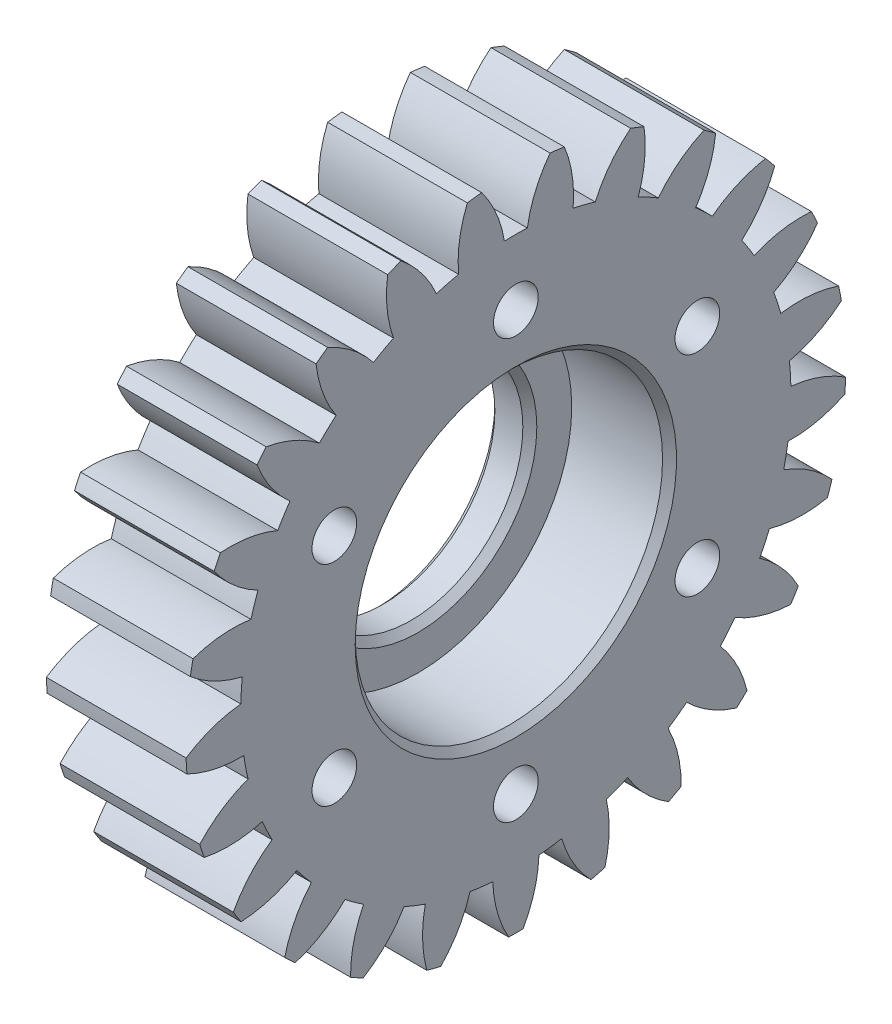
SolidWorks part; units mm, degrees
ref_plane "Plane1" through (0, 0, 0) normal (0, 0, 1) x (1, 0, 0)
ref_plane "Plane2" through (0, 0, 0) normal (0, 1, 0) x (1, 0, 0)
ref_plane "Plane3" through (0, 0, 0) normal (1, 0, 0) x (0, 0, -1)
sketch "HoldingSke" plane through (0, 0, 0) normal (0, 1, 0) x (1, 0, 0)
  line L0 (0, 0) -> (0.5179, -0.2415)
  line L1 (-15, 0) -> (100, 0) construction
  line L2 (0, 0) -> (-2.1039, 2.3779)
  line L3 (0, 0) -> (-11.863, 4.5341)
  line L4 (0, 0) -> (7.8269, 3.6497)
  line L5 (0, 0) -> (-46.8476, -17.4728)
  line L6 (0, 0) -> (-8.2896, -5.593)
  line L7 (-2.1039, 2.3779) -> (8.6586, 51.2059)
  line L8 (-76.2, 54.61) -> (-74.8, 54.61)
  line L9 (-71.009, 38.7566) -> (-53.1078, 45.2721)
  line L10 (-76.2, 71.12) -> (104.1128, 71.12)
  line L11 (0, 0) -> (-10, 0)
  line L12 (-76.2, 101.6) -> (-76.147, 101.6)
  line L13 (24.9733, 27.94) -> (52.9518, 28.4284)
  line L14 (24.9733, 27.94) -> (24.9743, 27.94)
  line L15 (24.9733, 27.94) -> (100.4006, 29.5858)
  line L16 (-63.627, -1.75) -> (-12.827, -1.75)
  circle A0 centre (0, 0) radius 4
  circle A1 centre (0, 0) radius 19.6865
  circle A2 centre (0, 0) radius 37.5
  circle A3 centre (0, 0) radius 4
  dimension "MHD" = 39.373
  dimension "Hub_dia" = 75
  dimension "Bore" = 8
  dimension "MBD" = 8
  dimension "Num_teeth" = 25
  dimension "Pitch" = 0.5714
  dimension "Overall_len" = 50
  dimension "Show_teeth" = 25
  dimension "Thickness" = 10
  dimension "OAL" = 50.0001
  dimension "T_dim" = 1.4
  dimension "Ap" = 20
  dimension "H" = 19.05
  dimension "Pitch_radius" = 180.3128
  dimension "Width" = 10
  dimension "Backlash" = 0.053
  dimension "Addendum_fac" = 1
  dimension "Dedendum_fac" = 1.25
  dimension "Clearance_fac" = 0.25
  dimension "Dedendum_add" = 0.001
  dimension "Module" = 1.75
sketch "BasProSke" plane through (0, 0, 0) normal (0, 1, 0) x (1, 0, 0)
  line L0 (-10, 0) -> (60, 0) construction
  line L1 (0, 0) -> (0, 23.625)
  line L2 (0, 0) -> (10, 0)
  line L3 (10, 0) -> (10, 23.625)
  line L4 (10, 23.625) -> (0, 23.625)
  dimension "Thickness" = 10
  dimension "Diameter" = 47.25
revolve "Base-Revolve" add sketch "BasProSke" angle 360 about L0
sketch "TooCutSke" plane through (0, 0, 0) normal (1, 0, 0) x (0, 0, -1)
  line L1 (0, 0) -> (0, 107) construction
  line L2 (0, 0) -> (-1.4663, 21.8258) construction
  line L3 (0, 0) -> (-5.4739, 43.3306) construction
  line L4 (-1.4663, 21.8258) -> (-2.737, 21.6653) construction
  arc A0 (0.819, 19.6695) -> (-0.819, 19.6695) centre (0, 0) ccw
  arc A1 (2.4674, 23.5213) -> (-2.4674, 23.5213) centre (0, 0) ccw
  circle A2 centre (0, 0) radius 21.875 construction
  circle A3 centre (0, 0) radius 20.5558 construction
  arc A4 (-0.819, 19.6695) -> (-2.4674, 23.5213) centre (-9.4536, 18.2529) ccw
  arc A5 (2.4674, 23.5213) -> (0.819, 19.6695) centre (9.4536, 18.2529) ccw
  dimension "Root_dia" = 39.373
  dimension "Overcut_dia" = 47.3008
  dimension "Pitch_dia" = 43.75
  dimension "Base_dia" = 41.1116
  dimension "Flank_rad" = 8.75
  dimension "Half_ang" = 7.2
  dimension "Half_CT" = 1.2808
extrude "ToothCut" cut sketch "TooCutSke" along normal through all
fillet "Breaks" [suppressed] radius 0.035
fillet "RootFillets" [suppressed] radius 0.4385
pattern_circular "TeethCuts" count 25 every 14.4 about axis through (-10, 0, 0) along (1, 0, 0) of "ToothCut", "RootFillets", "Breaks"
sketch "HubNeaOneSke" plane through (0, 0, 0) normal (-1, 0, 0) x (0, 0, 1)
  circle A0 centre (0, 0) radius 19.6865
  dimension "Diameter" = 39.373
extrude "HubNearOne" [suppressed] add sketch "HubNeaOneSke" along normal blind 40.0001
sketch "HubNeaBotSke" plane through (0, 0, 0) normal (-1, 0, 0) x (0, 0, 1)
  circle A0 centre (0, 0) radius 19.6865
  dimension "Diameter" = 39.373
extrude "HubNearBoth" [suppressed] add sketch "HubNeaBotSke" along normal blind 20
ref_plane "FarPln" through (10, 0, 0) normal (1, 0, 0) x (0, 0, -1)
sketch "HubFarSke" plane through (10, 0, 0) normal (1, 0, 0) x (0, 0, -1)
  circle A0 centre (0, 0) radius 19.6865
  dimension "Diameter" = 39.373
extrude "HubFar" [suppressed] add sketch "HubFarSke" along normal blind 20
sketch "BorSke" plane through (0, 0, 0) normal (1, 0, 0) x (0, 0, -1)
  circle A0 centre (0, 0) radius 4
  dimension "Diameter" = 8
extrude "Bore" cut sketch "BorSke" along normal mid plane 100.0001
sketch "KeySke" plane through (0, 0, 0) normal (1, 0, 0) x (0, 0, -1)
  line L0 (-1.5, 0) -> (-1.5, 5.4)
  line L1 (-1.5, 5.4) -> (1.5, 5.4)
  line L2 (1.5, 5.4) -> (1.5, 0)
  line L3 (0, 0) -> (0, 34) construction
  line L4 (-1.5, 0) -> (1.5, 0)
  dimension "Offset" = 5.4
  dimension "Width" = 3
extrude "Keyway" [suppressed] cut sketch "KeySke" along normal mid plane 100.0001
pattern_circular "Keyway2" [suppressed] count 2 every 90 about axis through (-10, 0, 0) along (1, 0, 0)
sketch "Sketch1" plane through (10, 0, 0) normal (1, 0, 0) x (0, 0, -1)
  circle A0 centre (0, 0) radius 11
  dimension "D1" = 22
extrude "Cut-Extrude1" cut sketch "Sketch1" against normal blind 7
sketch "Sketch2" plane through (3, 0, 0) normal (1, 0, 0) x (0, 0, -1)
  circle A0 centre (0, 0) radius 8
  dimension "D1" = 16
extrude "Cut-Extrude2" cut sketch "Sketch2" against normal up to next
sketch "Sketch3" plane through (10, 0, 0) normal (1, 0, 0) x (0, 0, -1)
  line L0 (0, 0) -> (0, 13.081) construction
  circle A0 centre (0, 15) radius 1.6
  dimension "D1" = 3.2
  dimension "D2" = 15
extrude "Cut-Extrude3" cut sketch "Sketch3" against normal up to next
pattern_circular "CirPattern1" count 6 over 360 about axis through (0, 0, 0) along (1, 0, 0) of "Cut-Extrude3"
chamfer "Chamfer1" distance 0.5 angle 45 3 edges at (10, 0, -11) (0, 0, -8) (3, 0, -8)
equation "' \"Module@HoldingSke\" = 6.35"
equation "' \"Num_teeth@HoldingSke\" = 12"
equation "' \"Ap@HoldingSke\" =  20"
equation "' \"Ap@HoldingSke\" = 20"
equation "' \"Width@HoldingSke\" = 0.5 * 25.4"
equation "' \"Hub_dia@HoldingSke\"= 1 * 25.4"
equation "' \"Hub_dia@HoldingSke\" = 1 * 25.4"
equation "' \"Overall_len@HoldingSke\" = 1.0 * 25.4"
equation "' \"Bore@HoldingSke\" = 0.75 * 25.4"
equation "' \"T_dim@HoldingSke\" = 0.1 * 25.4"
equation "' \"Width@KeySke\" = 0.25 * 25.4"
equation "' \"Show_teeth@HoldingSke\" = 13"
equation "' \"Backlash@HoldingSke\" = 0.009 * 25.4"
equation "' \"Addendum_fac@HoldingSke\" = 1.0"
equation "' \"Dedendum_fac@HoldingSke\" = 1.25"
equation "' \"Dedendum_add@HoldingSke\" = 0.00005 * 25.4"
equation "' \"Clearance_fac@HoldingSke\" = 0.25"
equation "\"Pitch@HoldingSke\" = 1 / \"Module@HoldingSke\""
equation "\"Overcut_dia@TooCutSke\" = (\"Num_teeth@HoldingSke\" + 2 * \"Addendum_fac@HoldingSke\") / \"Pitch@HoldingSke\" + 0.002 * 25.4"
equation "\"Pitch_dia@TooCutSke\" = \"Num_teeth@HoldingSke\" / \"Pitch@HoldingSke\""
equation "\"Base_dia@TooCutSke\" = \"Num_teeth@HoldingSke\" / \"Pitch@HoldingSke\" * cos((\"Ap@HoldingSke\"  * 3.14159265 / 180))"
equation "\"Root_dia@TooCutSke\" = (\"Num_teeth@HoldingSke\" + 2) / \"Pitch@HoldingSke\" - 2 * (\"Addendum_fac@HoldingSke\" + \"Dedendum_fac@HoldingSke\") / \"Pitch@HoldingSke\" - \"Dedendum_add@HoldingSke\" * 2"
equation "\"Half_ang@TooCutSke\" = 180 / \"Num_teeth@HoldingSke\""
equation "\"Half_CT@TooCutSke\" = \"Num_teeth@HoldingSke\" / \"Pitch@HoldingSke\" * sin((3.14159265 / 2 / \"Num_teeth@HoldingSke\")) / 2 - 7 * \"Backlash@HoldingSke\" / 4"
equation "\"Flank_rad@TooCutSke\" = \"Num_teeth@HoldingSke\" / \"Pitch@HoldingSke\" / 5"
equation "\"Radius@RootFillets\" = \"Clearance_fac@HoldingSke\" / \"Pitch@HoldingSke\" + \"Dedendum_add@HoldingSke\""
equation "\"Break_rad@Breaks\" = 0.02 / \"Pitch@HoldingSke\""
equation "\"Thickness@HoldingSke\" = \"Width@HoldingSke\""
equation "\"OAL@HoldingSke\" = \"Thickness@HoldingSke\""
equation "\"MHD@HoldingSke\" = (\"Num_teeth@HoldingSke\" + 2) / \"Pitch@HoldingSke\" - 2 * (\"Addendum_fac@HoldingSke\" + \"Dedendum_fac@HoldingSke\")  / \"Pitch@HoldingSke\" - \"Dedendum_add@HoldingSke\" * 2"
equation "\"MBD@HoldingSke\" = (\"Num_teeth@HoldingSke\" + 2) / \"Pitch@HoldingSke\" - 2 * (\"Addendum_fac@HoldingSke\" + \"Dedendum_fac@HoldingSke\")  / \"Pitch@HoldingSke\" - \"Dedendum_add@HoldingSke\" * 2 - 0.002 * 25.4"
equation "\"MHD@HoldingSke\" = ((sgn( \"MHD@HoldingSke\" - \"Hub_dia@HoldingSke\" )-1)*( \"MHD@HoldingSke\" - \"Hub_dia@HoldingSke\" ))/-2+ \"Hub_dia@HoldingSke\""
equation "\"MBD@HoldingSke\" = ((sgn( \"MBD@HoldingSke\" - \"Bore@HoldingSke\" )-1)*( \"MBD@HoldingSke\" - \"Bore@HoldingSke\" ))/-2+ \"Bore@HoldingSke\""
equation "\"OAL@HoldingSke\" = ((sgn( \"OAL@HoldingSke\" - \"Overall_len@HoldingSke\" )+1)*( \"OAL@HoldingSke\" - \"Overall_len@HoldingSke\" ))/2 + \"Overall_len@HoldingSke\" + 0.000002 * 25.4"
equation "\"Num_teeth@TeethCuts\" = int( \"Show_teeth@HoldingSke\" ) + 1"
equation "\"Num_teeth@TeethCuts\" = ((sgn( \"Num_teeth@TeethCuts\" - \"Num_teeth@HoldingSke\" )-1)*( \"Num_teeth@TeethCuts\" - \"Num_teeth@HoldingSke\" ))/-2+ \"Num_teeth@HoldingSke\""
equation "\"Num_teeth@TeethCuts\" = ((sgn( \"Num_teeth@TeethCuts\" - 2.0)+1)*( \"Num_teeth@TeethCuts\" - 2.0))/2 +2.0"
equation "\"Angle@TeethCuts\" = 360.0 / \"Num_teeth@HoldingSke\""
equation "\"Diameter@BasProSke\" = (\"Num_teeth@HoldingSke\" + 2 * \"Addendum_fac@HoldingSke\") / \"Pitch@HoldingSke\""
equation "\"Thickness@BasProSke\"  = \"Thickness@HoldingSke\""
equation "' \"Fillet_rad@BasProSke\" =  \"Thickness@HoldingSke\" * 0.05"
equation "' \"Fillet_rad@BasProSke\" = \"Thickness@HoldingSke\" * 0.05"
equation "\"MHD@HoldingSke\" = ((sgn( \"MHD@HoldingSke\" - \"Root_dia@TooCutSke\" )-1)*( \"MHD@HoldingSke\" - \"Root_dia@TooCutSke\" ))/-2+ \"Root_dia@TooCutSke\""
equation "\"Diameter@HubNeaOneSke\" = \"MHD@HoldingSke\""
equation "\"Length@HubNearOne\" = \"OAL@HoldingSke\" - \"Thickness@BasProSke\""
equation "\"Diameter@HubNeaBotSke\" = \"MHD@HoldingSke\""
equation "\"Length@HubNearBoth\" = ( \"OAL@HoldingSke\" - \"Thickness@BasProSke\" ) / 2.0"
equation "\"Thickness@FarPln\" = \"Thickness@BasProSke\""
equation "\"Diameter@HubFarSke\" = \"MHD@HoldingSke\""
equation "\"Length@HubFar\" = ( \"OAL@HoldingSke\" - \"Thickness@BasProSke\" ) / 2.0"
equation "\"Diameter@BorSke\" = \"MBD@HoldingSke\""
equation "\"D1@Bore\" = \"OAL@HoldingSke\" * 2.0"
equation "\"D1@Keyway\" = \"OAL@HoldingSke\" * 2.0"
equation "\"Offset@KeySke\" = \"T_dim@HoldingSke\" + \"MBD@HoldingSke\" / 2.0"
